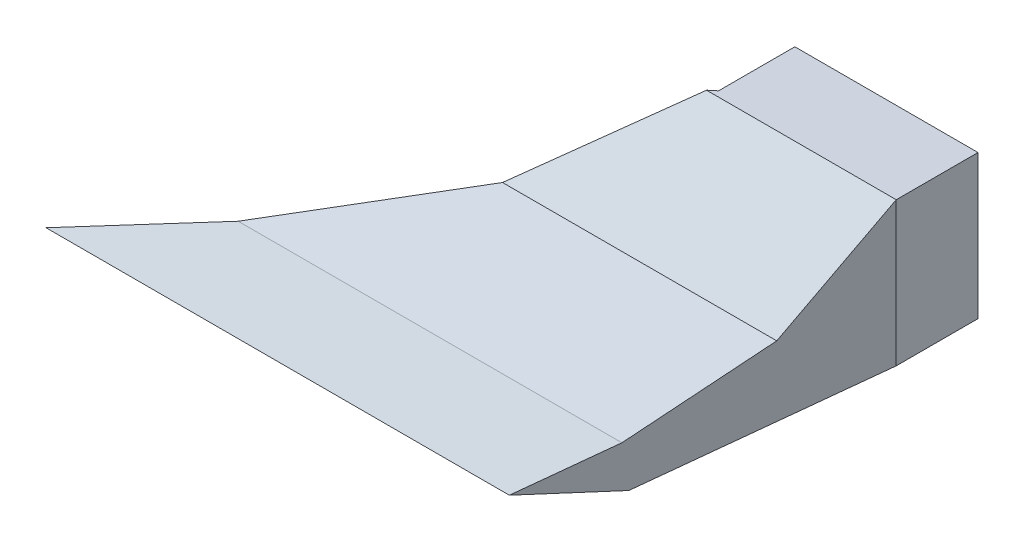
SolidWorks part; units mm, degrees
ref_plane "Front"
ref_plane "Top" through (0, 0, 0) normal (0, 1, 0) x (1, 0, 0)
ref_plane "Right" through (0, 0, 0) normal (1, 0, 0) x (0, 0, -1)
sketch "Side base sketch" plane through (0, 0, 0) normal (-1, 0, 0) x (0, 0, 1)
  line L0 (0, 13.2) -> (8.4913, 5)
  line L1 (0, 0) -> (6, -1)
  line L2 (6, -1) -> (19, -3.1667)
  line L3 (8.4913, 5) -> (19.4913, 0.803)
  line L4 (19.4913, 0.803) -> (27.4913, -0.5303)
  line L5 (27.4913, -0.5303) -> (19, -3.1667)
  line L6 (0, 13.2) -> (0, 0)
  dimension "D1" = 6
  dimension "D2" = 6
  dimension "D3" = 1
  dimension "D4" = 46
  dimension "D5" = 13
  dimension "D6" = 11
  dimension "D7" = 4
  dimension "D8" = 8
  dimension "D9" = 13.2
extrude "Side base" add sketch "Side base sketch" against normal blind 0.5
pattern_linear "Side base 2" count 2 spacing 50 along (1, 0, 0) of bodies 108
sketch "Wall base sketch" plane through (0.5, 0, 0) normal (1, 0, 0) x (0, 0, -1)
  line L0 (0, 12.5049) -> (-8.2176, 4.5693)
  line L1 (-26.429, -0.8601) -> (-19.3598, 0.3181)
  line L2 (-27.4913, -0.5303) -> (-19.4913, 0.803)
  line L3 (-19, -3.4019) -> (-19, 4.6777) construction
  line L4 (0, 13.2) -> (0, 0) construction
  line L5 (0, 0) -> (-19, -3.1667) construction
  line L6 (-19.4913, 0.803) -> (-8.4913, 5)
  line L7 (-19.3598, 0.3181) -> (-8.2176, 4.5693)
  line L8 (-8.4913, 5) -> (0, 13.2) construction
  line L9 (0, 0.5069) -> (-19, -2.6598)
  line L11 (-19, -2.6598) -> (-19, -3.1667)
  line L12 (-19, -3.1667) -> (0, 0)
  line L13 (0, 0) -> (0, 0.5069)
  line L14 (-26.429, -0.8601) -> (-27.4913, -0.5303)
  line L16 (-8.4913, 5) -> (0, 13.2)
  line L17 (0, 13.2) -> (0, 12.5049)
  line L18 (-19, -3.1667) -> (-27.4913, -0.5303) construction
  point P2 (-19.4913, 0.803)
  point P4 (-19.3598, 0.3181)
  dimension "D1" = 0.5
  dimension "D2" = 0.5
  dimension "D3" = 0.5
  dimension "D4" = 0.5
extrude "Front back walls" add sketch "Wall base sketch" along normal up to next
sketch "Base sketch" plane through (0, 0, 0) normal (0, 0, -1) x (-1, 0, 0)
  line L0 (-50, 12.5049) -> (-0.5, 12.5049) construction
  line L1 (0, 13.2) -> (-50.5, 13.2)
  line L2 (0, 13.2) -> (0, 0)
  line L3 (0, 0) -> (-50.5, 0)
  line L4 (-50.5, 13.2) -> (-50.5, 0)
  line L5 (-50, 0.5069) -> (-34.2, 0.5069)
  line L6 (-50, 0.5069) -> (-50, 12.5049)
  line L7 (-50, 12.5049) -> (-34.2, 12.5049)
  line L8 (-34.2, 0.5069) -> (-34.2, 12.5049)
  dimension "D1" = 15.8
extrude "Base" add sketch "Base sketch" along normal blind 0.5
sketch "Attachment base sketch" plane through (0, 0, -0.5) normal (0, 0, -1) x (-1, 0, 0)
  line L0 (-50.5, 0) -> (0, 0) construction
  line L1 (-50.5, 13.2) -> (-33.7, 13.2)
  line L2 (-50.5, 13.2) -> (-50.5, 0)
  line L3 (-50.5, 0) -> (-33.7, 0)
  line L4 (-33.7, 13.2) -> (-33.7, 0)
  line L5 (-34.2, 0.5069) -> (-34.2, 12.5049) construction
  line L7 (-34.2, 12.5049) -> (-50, 12.5049)
  line L8 (-34.2, 12.5049) -> (-34.2, 0.5069)
  line L9 (-34.2, 0.5069) -> (-50, 0.5069)
  line L10 (-50, 12.5049) -> (-50, 0.5069)
  dimension "D1" = 0.5
extrude "Attachment base" add sketch "Attachment base sketch" along normal blind 7
sketch "Sketch11" plane through (0, 0, -7.5) normal (0, 0, -1) x (-1, 0, 0)
  line L0 (-33.7, 13.2) -> (-50.5, 13.2) construction
  line L1 (-50, 12.5049) -> (-34.2, 12.5049)
  line L2 (-50, 12.5049) -> (-50, 12.7)
  line L3 (-50, 12.7) -> (-34.2, 12.7)
  line L4 (-34.2, 12.5049) -> (-34.2, 12.7)
  dimension "D1" = 0.5
extrude "Pipe top extra cutaway" cut sketch "Sketch11" against normal up to surface (7.5 mm away)
sketch "Sketch1" plane through (0, 0, -7.5) normal (0, 0, -1) x (-1, 0, 0)
  line L0 (-50, 12.7) -> (-50, 0.5069) construction
  line L1 (-50, 12.7) -> (-34.2, 12.7)
  line L2 (-50, 12.7) -> (-50, 0.5069)
  line L3 (-50, 0.5069) -> (-34.2, 0.5069)
  line L4 (-34.2, 12.7) -> (-34.2, 0.5069)
extrude "Fan base" add sketch "Sketch1" along normal blind 0.1 separate body
sketch "Sketch4" plane through (0.5, 0, 0) normal (1, 0, 0) x (0, 0, -1)
  line L0 (-26.429, -0.8601) -> (-19, -3.1667)
  line L1 (-19, -3.1667) -> (-19, -2.6598)
  line L2 (-19, -2.6598) -> (0, 0.5069)
  line L3 (0, 0.5069) -> (0, 12.5049)
  line L4 (-8.2176, 4.5693) -> (0, 12.5049) construction
  line L5 (0, 12.5049) -> (0, 0.5069) construction
  line L6 (0, 12.5049) -> (-8.2176, 4.5693)
  line L7 (-8.2176, 4.5693) -> (-19.3598, 0.3181)
  line L8 (-26.429, -0.8601) -> (-19.3598, 0.3181)
extrude "Left right wall removal" cut sketch "Sketch4" against normal through all both and the other way through all
ref_point "Cutaway left intersection point" parameters "D1"=8
ref_plane "Cutaway left plane" through (46.5575, 0, 13.5482) normal (0.9602, 0, 0.2794) x (0.2794, 0, -0.9602)
sketch "Sketch6" plane through (46.5575, 0, 13.5482) normal (0.9602, 0, 0.2794) x (0.2794, 0, -0.9602)
  line L1 (-14.5215, -3.1667) -> (14.1102, -3.1667)
  line L2 (-14.5215, -3.1667) -> (-14.5215, 13.2)
  line L3 (-14.5215, 13.2) -> (14.1102, 13.2)
  line L4 (14.1102, -3.1667) -> (14.1102, 13.2)
  point P4 (-14.5215, -0.5303)
  point P6 (-5.6779, -3.1667)
extrude "Cutaway left" cut sketch "Sketch6" along normal through all
sketch "Sketch7" plane through (46.5575, 0, 13.5482) normal (0.9602, 0, 0.2794) x (0.2794, 0, -0.9602)
  line L0 (-5.6779, -2.6598) -> (-5.6779, -3.1667)
  line L1 (-5.6779, -3.1667) -> (-13.415, -0.8601)
  line L2 (-13.415, -0.8601) -> (-6.0526, 0.3181)
  line L3 (5.5518, 4.5693) -> (14.1102, 12.5049)
  line L4 (14.1102, 12.5049) -> (14.1102, 0.5069)
  line L5 (14.1102, 0.5069) -> (-5.6779, -2.6598)
  line L6 (-6.0526, 0.3181) -> (5.5518, 4.5693)
extrude "Left wall" add sketch "Sketch7" along direction (-1, 0, 0) on the side against the normal blind 0.5207
ref_point "Cutaway right intersection point 1" parameters "D1"=4
ref_point "Cutaway right intersection point 2" parameters "D1"=4
ref_plane "Cutaway right plane" through (13.5123, 0, 16.268) normal (0.6389, 0, 0.7693) x (0.7693, 0, -0.6389)
sketch "Sketch9" plane through (13.5123, 0, 16.268) normal (0.6389, 0, 0.7693) x (0.7693, 0, -0.6389)
  line L1 (26.2433, 13.2) -> (-17.5654, 13.2)
  line L2 (26.2433, 13.2) -> (26.2433, -3.1667)
  line L3 (26.2433, -3.1667) -> (-17.5654, -3.1667)
  line L4 (-17.5654, 13.2) -> (-17.5654, -3.1667)
extrude "Cutaway right" cut sketch "Sketch9" against normal through all
sketch "Sketch10" plane through (13.5123, 0, 16.268) normal (-0.6389, 0, -0.7693) x (-0.7693, 0, 0.6389)
  line L0 (-25.4608, 12.5049) -> (-25.4608, 0.5069)
  line L1 (-25.4608, 0.5069) -> (4.2758, -2.6598)
  line L2 (4.2758, -2.6598) -> (4.2758, -3.1667)
  line L3 (4.2758, -3.1667) -> (15.9028, -0.8601)
  line L4 (15.9028, -0.8601) -> (4.839, 0.3181)
  line L5 (-12.5996, 4.5693) -> (-25.4608, 12.5049)
  line L6 (4.839, 0.3181) -> (-12.5996, 4.5693)
extrude "Right wall" add sketch "Sketch10" along direction (-1, 0, 0) on the side against the normal blind 0.7817
ref_plane "Air flow cut plane" through (0, 0, 27.4913) normal (0, 0, 1) x (1, 0, 0)
delete or keep bodies "Body-Delete/Keep 1" type delete bodies bodies 129
equation "\"wall_thicknes\"= 0.5"
equation "\"D1@Base\" = \"wall_thicknes\""
equation "\"D1@Wall base sketch\"=\"wall_thicknes\""
equation "\"D1@Side base\"=\"wall_thicknes\""
equation "\"D2@Wall base sketch\"=\"wall_thicknes\""
equation "\"D3@Wall base sketch\"=\"wall_thicknes\""
equation "\"D1@Base sketch\"=\"wall_thicknes\"*-2+16.8"
equation "\"D1@Attachment base sketch\"=\"wall_thicknes\""
equation "\"D1@Left wall\"=\"left_wall_thickness\""
equation "\"D1@Sketch11\"=\"wall_thicknes\""
equation "\"left_wall_thickness\" = 0.83318430202930948562 * 0.625"
equation "\"right_wall_thickness\" = 1.25073472653581935106 * 0.625"
equation "\"D1@Right wall\"=\"right_wall_thickness\""
equation "\"D4@Wall base sketch\"=\"wall_thicknes\""
